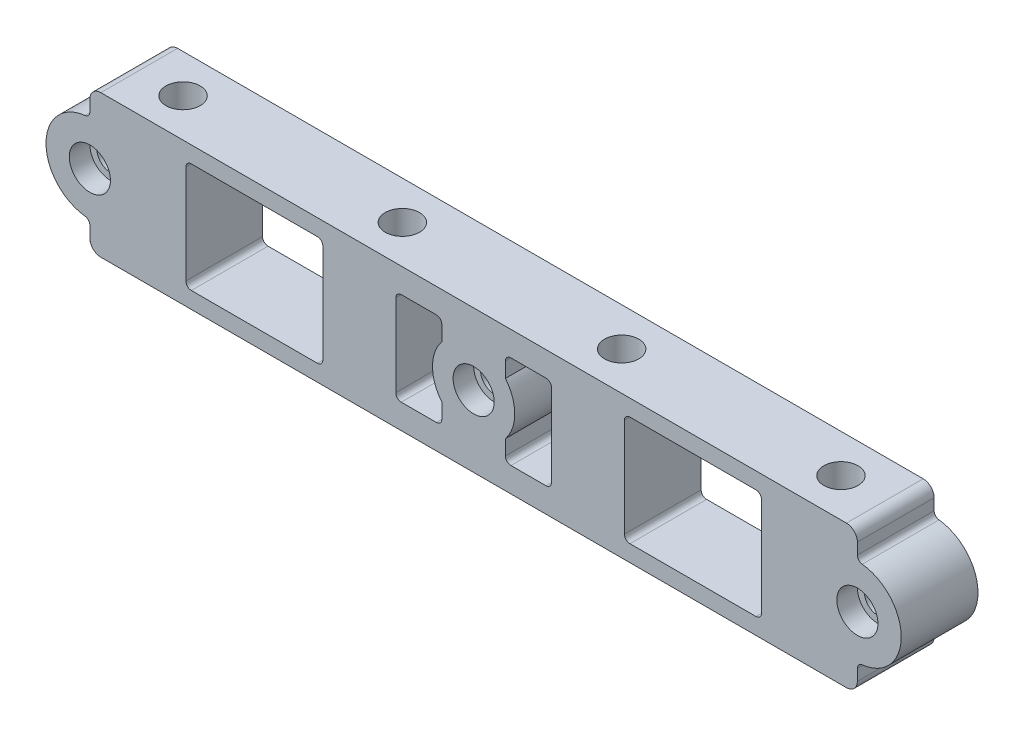
SolidWorks part; units mm, degrees
material "6061-T6 (SS)"
ref_plane "X-Y Datum" through (0, 0, 0) normal (0, 0, 1) x (1, 0, 0)
ref_plane "X-Z Datum" through (0, 0, 0) normal (0, 1, 0) x (1, 0, 0)
ref_plane "Y-Z Datum" through (0, 0, 0) normal (1, 0, 0) x (0, 0, -1)
other "Graphic1"
other "Graphic (Closed) -1"
other "Graphic2"
other "Graphic (Closed) -2"
other "Graphic3"
other "Graphic (Closed) -3"
sketch "Sketch1" plane through (0, 0, 0) normal (0, 1, 0) x (1, 0, 0)
  line L0 (101.6, 8.89) -> (76.2, 8.89) construction
  line L1 (101.6, 17.78) -> (-101.6, 17.78)
  line L2 (101.6, 17.78) -> (101.6, 0)
  line L3 (101.6, 0) -> (-101.6, 0)
  line L4 (-101.6, 17.78) -> (-101.6, 0)
  line L7 (76.2, 8.89) -> (25.4, 8.89) construction
  line L8 (25.4, 8.89) -> (-25.4, 8.89) construction
  line L9 (-25.4, 8.89) -> (-76.2, 8.89) construction
  line L10 (-76.2, 8.89) -> (-101.6, 8.89) construction
  circle A0 centre (76.2, 8.89) radius 3.9688
  circle A1 centre (25.4, 8.89) radius 3.9687
  circle A2 centre (-25.4, 8.89) radius 3.9687
  circle A3 centre (-76.2, 8.89) radius 3.9688
  point P0 (0, 0)
  point P19 (0, 8.89)
  dimension "D3" = 7.9375
  dimension "D1" = 203.2
  dimension "D2" = 17.78
  dimension "D4" = 50.8
  dimension "D5" = 25.4
extrude "Boss-Extrude1" add sketch "Sketch1" against normal blind 33.02
sketch "Sketch2" plane through (0, 0, 0) normal (0, 0, 1) x (1, 0, 0)
  line L0 (80.1687, 0) -> (80.1687, -33.02) construction
  line L1 (-101.6, 0) -> (101.6, 0) construction
  line L2 (-101.6, -33.02) -> (101.6, -33.02) construction
  line L3 (72.2312, 0) -> (72.2312, -33.02) construction
  line L4 (-72.2313, 0) -> (-72.2313, -33.02) construction
  line L5 (-80.1687, 0) -> (-80.1687, -33.02) construction
  line L6 (80.1687, 0) -> (72.2312, 0) construction
  line L7 (80.1687, 0) -> (72.2312, 0) construction
  line L8 (-72.2313, 0) -> (-80.1687, 0) construction
  line L9 (-72.2312, 0) -> (-80.1688, 0) construction
  line L10 (80.1687, -16.51) -> (72.2312, -16.51) construction
  line L11 (-72.2313, -16.51) -> (-80.1687, -16.51) construction
  line L12 (-101.6, -33.02) -> (-101.6, 0) construction
  circle A0 centre (88.9, -16.51) radius 3.175
  circle A1 centre (0, -16.51) radius 3.175
  circle A2 centre (-88.9, -16.51) radius 3.175
  point P12 (76.2, 0)
  point P15 (-76.2, 0)
  point P26 (76.2, -16.51)
  point P27 (-76.2, -16.51)
  point P37 (-101.6, -16.51)
  dimension "D3" = 6.35
  dimension "D1" = 7.9375
  dimension "D2" = 7.9375
  dimension "D4" = 12.7
  dimension "D5" = 12.7
extrude "Cut-Extrude1" cut sketch "Sketch2" against normal up to surface (17.78 mm away) up to face at (0, -16.51, -17.78)
sketch "Sketch3" plane through (0, 0, 0) normal (0, 0, 1) x (1, 0, 0)
  circle A0 centre (88.9, -16.51) radius 4.7625
  circle A1 centre (0, -16.51) radius 4.7625
  circle A2 centre (-88.9, -16.51) radius 4.7625
  dimension "D1" = 9.525
extrude "Cut-Extrude2" cut sketch "Sketch3" against normal blind 4.7752
ref_plane "Plane1" through (0, -16.51, 0) normal (0, 1, 0) x (1, 0, 0)
ref_plane "Plane2" through (0, -16.51, 0) normal (0, 1, 0) x (1, 0, 0)
ref_point "Point1"
ref_point "Point2"
ref_point "Point3"
ref_point "Point4"
sketch "Sketch4" plane through (0, 0, 0) normal (0, 0, 1) x (1, 0, 0)
  line L0 (0, 0) -> (0, -33.02) construction
  line L1 (-36.195, -29.21) -> (-65.405, -29.21)
  line L2 (-34.925, -27.94) -> (-34.925, -5.08)
  line L3 (-36.195, -3.81) -> (-65.405, -3.81)
  line L4 (-66.675, -27.94) -> (-66.675, -5.08)
  line L5 (-8.636, -27.305) -> (-16.764, -27.305)
  line L6 (-7.366, -26.035) -> (-7.366, -22.5488)
  line L7 (-8.636, -5.715) -> (-16.764, -5.715)
  line L8 (-18.034, -26.035) -> (-18.034, -6.985)
  line L9 (-101.6, -33.02) -> (101.6, -33.02) construction
  line L10 (0, -16.51) -> (-101.6, -16.51) construction
  line L11 (-101.6, -33.02) -> (-101.6, 0) construction
  line L12 (-7.366, -10.4712) -> (-7.366, -6.985)
  line L13 (36.195, -3.81) -> (65.405, -3.81)
  line L14 (66.675, -27.94) -> (66.675, -5.08)
  line L15 (36.195, -29.21) -> (65.405, -29.21)
  line L16 (34.925, -27.94) -> (34.925, -5.08)
  line L17 (7.366, -26.035) -> (7.366, -22.5488)
  line L18 (8.636, -27.305) -> (16.764, -27.305)
  line L19 (18.034, -26.035) -> (18.034, -6.985)
  line L20 (8.636, -5.715) -> (16.764, -5.715)
  line L21 (7.366, -10.4712) -> (7.366, -6.985)
  arc A0 (-7.366, -22.5488) -> (-7.366, -10.4712) centre (0, -16.51) cw
  arc A1 (-66.675, -27.94) -> (-65.405, -29.21) centre (-65.405, -27.94) ccw
  arc A2 (-66.675, -5.08) -> (-65.405, -3.81) centre (-65.405, -5.08) cw
  arc A3 (-36.195, -3.81) -> (-34.925, -5.08) centre (-36.195, -5.08) cw
  arc A4 (-34.925, -27.94) -> (-36.195, -29.21) centre (-36.195, -27.94) cw
  arc A5 (-18.034, -6.985) -> (-16.764, -5.715) centre (-16.764, -6.985) cw
  arc A6 (-18.034, -26.035) -> (-16.764, -27.305) centre (-16.764, -26.035) ccw
  arc A7 (-8.636, -5.715) -> (-7.366, -6.985) centre (-8.636, -6.985) cw
  arc A8 (-8.636, -27.305) -> (-7.366, -26.035) centre (-8.636, -26.035) ccw
  arc A9 (66.675, -5.08) -> (65.405, -3.81) centre (65.405, -5.08) ccw
  arc A10 (66.675, -27.94) -> (65.405, -29.21) centre (65.405, -27.94) cw
  arc A11 (36.195, -3.81) -> (34.925, -5.08) centre (36.195, -5.08) ccw
  arc A12 (34.925, -27.94) -> (36.195, -29.21) centre (36.195, -27.94) ccw
  arc A13 (7.366, -22.5488) -> (7.366, -10.4712) centre (0, -16.51) ccw
  arc A14 (8.636, -27.305) -> (7.366, -26.035) centre (8.636, -26.035) cw
  arc A15 (18.034, -26.035) -> (16.764, -27.305) centre (16.764, -26.035) cw
  arc A16 (18.034, -6.985) -> (16.764, -5.715) centre (16.764, -6.985) ccw
  arc A17 (8.636, -5.715) -> (7.366, -6.985) centre (8.636, -6.985) ccw
  point P4 (-50.8, -29.21)
  point P13 (-34.925, -16.51)
  point P19 (-12.7, -27.305)
  point P25 (-66.675, -29.21)
  point P28 (-66.675, -3.81)
  point P33 (-34.925, -29.21)
  point P36 (-18.034, -5.715)
  point P39 (-18.034, -27.305)
  point P42 (-7.366, -5.715)
  dimension "D7" = 9.525
  dimension "D8" = 1.27
  dimension "D1" = 31.75
  dimension "D2" = 50.8
  dimension "D3" = 25.4
  dimension "D4" = 12.7
  dimension "D5" = 10.668
  dimension "D6" = 21.59
extrude "Cut-Extrude3" cut sketch "Sketch4" against normal up to surface (17.78 mm away) up to face at (85.725, -16.51, -17.78)
sketch "Sketch5" plane through (0, 0, 0) normal (0, 0, 1) x (1, 0, 0)
  line L0 (88.9, -33.02) -> (88.9, 0) construction
  line L1 (-101.6, -33.02) -> (101.6, -33.02) construction
  line L2 (88.9, -27.8692) -> (88.9, -33.02)
  line L3 (88.9, -5.1508) -> (88.9, 0)
  line L4 (-101.6, 0) -> (101.6, 0) construction
  line L5 (88.9, -33.02) -> (101.6, -33.02)
  line L6 (101.6, -33.02) -> (101.6, 0)
  line L7 (101.6, 0) -> (88.9, 0)
  line L8 (0, 0) -> (0, -33.02) construction
  line L9 (-88.9, -5.1508) -> (-88.9, 0)
  line L10 (-101.6, 0) -> (-88.9, 0)
  line L11 (-101.6, -33.02) -> (-101.6, 0)
  line L12 (-88.9, -33.02) -> (-101.6, -33.02)
  line L13 (-88.9, -27.8692) -> (-88.9, -33.02)
  arc A1 (90.0289, -26.6071) -> (90.0289, -6.4129) centre (88.9, -16.51) ccw
  arc A2 (88.9, -5.1508) -> (90.0289, -6.4129) centre (90.17, -5.1508) ccw
  arc A3 (88.9, -27.8692) -> (90.0289, -26.6071) centre (90.17, -27.8692) cw
  arc A4 (-88.9, -5.1508) -> (-90.0289, -6.4129) centre (-90.17, -5.1508) cw
  arc A5 (-88.9, -27.8692) -> (-90.0289, -26.6071) centre (-90.17, -27.8692) ccw
  arc A6 (-90.0289, -26.6071) -> (-90.0289, -6.4129) centre (-88.9, -16.51) cw
  point P10 (88.9, -16.51)
  point P19 (88.9, -26.67)
  dimension "D2" = 1.27
  dimension "D1" = 6.35
extrude "Cut-Extrude4" cut sketch "Sketch5" against normal up to surface (17.78 mm away) up to face at (11.8491, -16.51, -17.78)
fillet "Fillet1" radius 2.54 4 edges at (88.9, -33.02, -8.89) (-88.9, -33.02, -8.89) (-88.9, 0, -8.89) (88.9, 0, -8.89)
